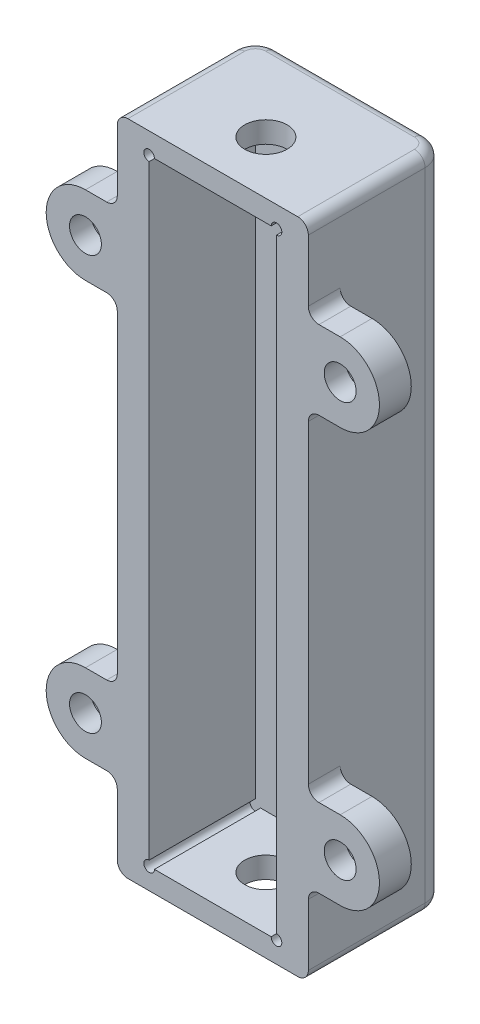
SolidWorks part; units mm, degrees
ref_plane "Plano frontal" through (0, 0, 0) normal (0, 0, 1) x (1, 0, 0)
ref_plane "Plano superior" through (0, 0, 0) normal (0, 1, 0) x (1, 0, 0)
ref_plane "Plano direito" through (0, 0, 0) normal (1, 0, 0) x (0, 0, -1)
sketch "Esboço1" plane through (0, 0, 0) normal (0, 1, 0) x (1, 0, 0)
  line L0 (-30.431, -40.7292) -> (-30.431, -41.2292)
  line L1 (-29.931, -31.2292) -> (-18.931, -31.2292)
  line L2 (-30.431, -31.7292) -> (-30.431, -40.7292)
  line L3 (-29.931, -41.2292) -> (-18.931, -41.2292)
  line L4 (-18.431, -31.7292) -> (-18.431, -40.7292)
  line L5 (-29.931, -41.2292) -> (-30.431, -41.2292)
  line L6 (-18.431, -40.7292) -> (-18.431, -41.2292)
  line L7 (-18.931, -41.2292) -> (-18.431, -41.2292)
  line L8 (-30.431, -31.7292) -> (-30.431, -31.6792)
  line L9 (-29.931, -31.2292) -> (-29.981, -31.2292)
  line L10 (-18.931, -31.2292) -> (-18.881, -31.2292)
  line L11 (-18.431, -31.7292) -> (-18.431, -31.6792)
  arc A0 (-29.981, -31.2292) -> (-30.431, -31.6792) centre (-29.981, -31.6792) ccw
  arc A1 (-18.431, -31.6792) -> (-18.881, -31.2292) centre (-18.881, -31.6792) ccw
  dimension "D1" = 0.45
  dimension "D2" = 0.45
extrude "Ressalto-extrusão1" add sketch "Esboço1" along normal blind 2
sketch "Esboço2" plane through (0, 2, 0) normal (0, 1, 0) x (1, 0, 0)
  line L0 (-18.881, -31.2292) -> (-29.981, -31.2292) construction
  line L2 (-30.431, -31.6792) -> (-30.431, -41.2292) construction
  circle A0 centre (-24.431, -36.2292) radius 2
  dimension "D1" = 5
  dimension "D2" = 6
extrude "Corte-extrusão1" cut sketch "Esboço2" against normal blind 2 contours A0
sketch "Esboço3" plane through (0, 2, 0) normal (0, 1, 0) x (1, 0, 0)
  line L2 (-29.931, -31.2292) -> (-29.981, -31.2292)
  line L3 (-30.431, -31.6792) -> (-30.431, -32.1722)
  line L4 (-30.431, -31.6792) -> (-30.431, -41.2292) construction
  line L5 (-30.431, -32.1722) -> (-30.431, -41.2292)
  line L6 (-30.431, -41.2292) -> (-33.431, -41.2292)
  line L7 (-29.931, -31.2292) -> (-18.881, -31.2292)
  line L8 (-18.431, -31.6792) -> (-18.431, -41.2292)
  line L9 (-18.431, -41.2292) -> (-15.431, -41.2292)
  line L11 (-33.431, -41.2292) -> (-33.431, -30.2292)
  line L12 (-15.431, -41.2292) -> (-15.431, -30.2292)
  line L13 (-31.431, -28.2292) -> (-17.431, -28.2292)
  arc A0 (-18.431, -31.6792) -> (-18.881, -31.2292) centre (-18.881, -31.6792) ccw
  arc A1 (-29.981, -31.2292) -> (-30.431, -31.6792) centre (-29.981, -31.6792) ccw
  arc A2 (-15.431, -30.2292) -> (-17.431, -28.2292) centre (-17.431, -30.2292) ccw
  arc A3 (-31.431, -28.2292) -> (-33.431, -30.2292) centre (-31.431, -30.2292) ccw
  dimension "D1" = 0.45
  dimension "D2" = 2
extrude "Ressalto-extrusão2" add sketch "Esboço3" against normal blind 62
sketch "Esboço4" plane through (0, 0, 41.2292) normal (0, 0, 1) x (1, 0, 0)
  line L0 (-33.431, -60) -> (-33.431, 2) construction
  line L1 (-36.431, -8) -> (-36.431, -5) construction
  line L2 (-36.431, -11) -> (-36.431, -14) construction
  line L3 (-36.431, -5.8) -> (-33.431, -5.8)
  line L4 (-36.431, -13.2) -> (-33.431, -13.2)
  circle A0 centre (-36.431, -9.5) radius 1.5
  arc A1 (-36.431, -5.8) -> (-36.431, -13.2) centre (-36.431, -9.5) ccw
  line M5 (-33.431, 2) -> (-33.431, -60)
  dimension "D1" = 3
extrude "Ressalto-extrusão4" add sketch "Esboço4" against normal blind 3 contours L3 A1 L4 A0 M5
fillet "Filete2" radius 1 2 edges at (-33.431, -13.2, 39.7292) (-33.431, -5.8, 39.7292)
ref_plane "Plano1" through (0, -29, 0) normal (0, 1, 0) x (1, 0, 0)
mirror "Espelhar1" about plane through (0, -29, 0) normal (0, 1, 0) of "Corte-extrusão1", "Ressalto-extrusão1"
fillet "Filete3" radius 1 10 edges at (-15.431, 2, 35.7292) (-15.431, -60, 35.7292) (-16.0168, 2, 28.8149) (-16.0168, -60, 28.8149) (-24.431, 2, 28.2292) (-24.431, -60, 28.2292) (-32.8453, 2, 28.8149) (-32.8453, -60, 28.8149) (-33.431, 2, 35.7292) (-33.431, -60, 35.7292)
ref_plane "Plano2" through (-24.431, 0, 0) normal (1, 0, 0) x (0, 0, -1)
sketch "Esboço6" plane through (0, 0, 38.2292) normal (0, 0, -1) x (-1, 0, 0)
  circle A0 centre (36.431, -9.5) radius 1.9
extrude "Corte-extrusão2" cut sketch "Esboço6" against normal blind 1
mirror "Espelhar2" about plane through (-24.431, 0, 0) normal (1, 0, 0) of "Ressalto-extrusão4", "Corte-extrusão2"
mirror "Espelhar3" about plane through (0, -29, 0) normal (0, 1, 0) of "Espelhar2", "Ressalto-extrusão4", "Corte-extrusão2"
fillet "Filete4" radius 1 6 edges at (-33.431, -44.8, 39.7292) (-33.431, -52.2, 39.7292) (-15.431, -44.8, 39.7292) (-15.431, -52.2, 39.7292) (-15.431, -5.8, 39.7292) (-15.431, -13.2, 39.7292)
sketch "Esboço7" plane through (0, 0, 41.2292) normal (0, 0, 1) x (1, 0, 0)
  line L0 (-30.431, 0) -> (-29.931, 0)
  line L1 (-30.431, 0) -> (-30.431, -0.5)
  arc A0 (-29.931, 0) -> (-30.431, -0.5) centre (-30.431, 0) ccw
  line M1 (-18.431, 0) -> (-18.431, -58)
  line M2 (-18.431, -58) -> (-30.431, -58)
  line M3 (-30.431, -58) -> (-30.431, 0)
  line M4 (-30.431, 0) -> (-18.431, 0)
extrude "Corte-extrusão3" cut sketch "Esboço7" against normal up to vertex and the other way through all contours M1 M4 M3 M2 | A0 M4 M3
mirror "Espelhar4" about plane through (-24.431, 0, 0) normal (1, 0, 0) of "Corte-extrusão3"
mirror "Espelhar5" about plane through (0, -29, 0) normal (0, 1, 0) of "Espelhar4", "Corte-extrusão3"
